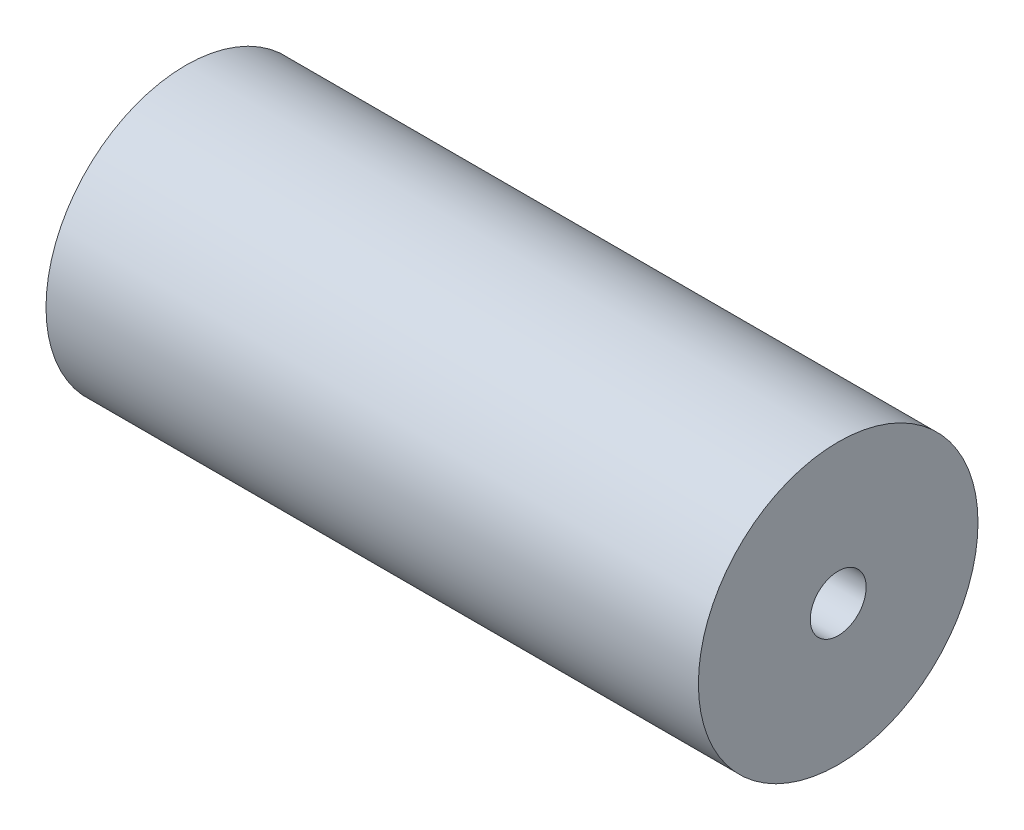
SolidWorks part; units mm, degrees
ref_plane "Front Plane" through (0, 0, 0) normal (0, 0, 1) x (1, 0, 0)
ref_plane "Top Plane" through (0, 0, 0) normal (0, 1, 0) x (1, 0, 0)
ref_plane "Right Plane" through (0, 0, 0) normal (1, 0, 0) x (0, 0, -1)
sketch "Sketch1" plane through (0, 0, 0) normal (0, 0, 1) x (1, 0, 0)
  line L0 (-22.225, 1.905) -> (22.225, 1.905)
  line L1 (-22.225, 0) -> (22.225, 0) construction
  line L2 (-22.225, 1.905) -> (-22.225, 9.525)
  line L3 (-22.225, 9.525) -> (22.225, 9.525)
  line L4 (22.225, 1.905) -> (22.225, 9.525)
  point P7 (0, 0)
  dimension "D1" = 3.81
  dimension "D2" = 19.05
  dimension "D3" = 44.45
revolve "Revolve1" add sketch "Sketch1" angle 360 about L1
